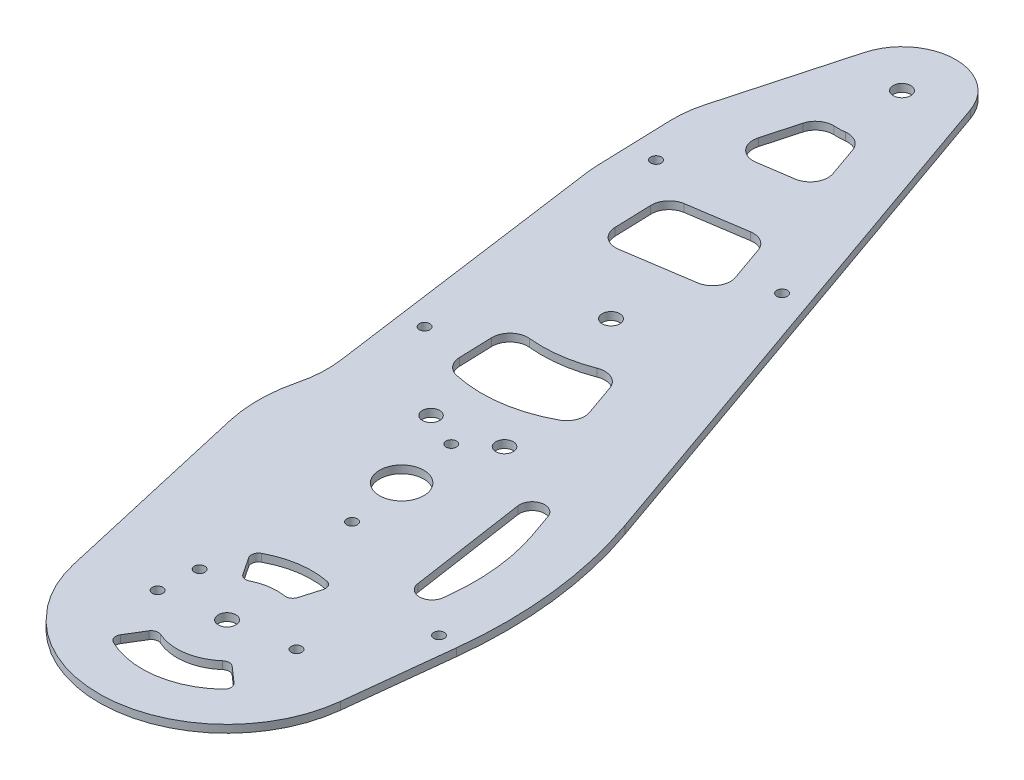
SolidWorks part; units mm, degrees
material "2024-T3"
ref_plane "Front Plane" through (0, 0, 0) normal (0, 0, 1) x (1, 0, 0)
ref_plane "Top Plane" through (0, 0, 0) normal (0, 1, 0) x (1, 0, 0)
ref_plane "Right Plane" through (0, 0, 0) normal (1, 0, 0) x (0, 0, -1)
sketch "Sketch1" plane through (0, 0, 0) normal (0, 1, 0) x (1, 0, 0)
  line L0 (-52.8408, -53.4809) -> (-39.9436, -109.9388)
  line L1 (30.3798, -105.849) -> (33.6155, -76.789)
  line L2 (27.5639, -23.7203) -> (-24.6842, 124.9398)
  line L3 (-53.2991, 123.942) -> (-62.8551, 89.1791)
  line L4 (-63.9122, 80.2517) -> (-63.23, 59.2843)
  line L5 (-62.9652, 56.1657) -> (-52.0063, -23.3829)
  line L6 (-41.9171, 82.2985) -> (-32.3997, 83.6985)
  line L7 (-44.7933, 98.2933) -> (-47.4659, 88.5706)
  line L8 (-28.4102, 90.3032) -> (-31.3828, 98.7609)
  line L9 (-16.9379, 51.6293) -> (-20.3906, 61.4534)
  line L10 (-45.8179, 46.898) -> (-46.153, 57.1955)
  line L11 (-41.9064, 62.3014) -> (-25.8585, 64.7388)
  line L12 (-40.0698, 42.1173) -> (-20.9042, 45.0281)
  line L13 (-4.685, -1.3287) -> (-7.7549, 7.4061)
  line L14 (-36.3858, 3.017) -> (-36.0858, -6.2051)
  line L15 (19.8444, -64.9197) -> (19.6676, -66.5078)
  line L16 (16.8186, -38.3853) -> (14.6523, -32.2214)
  line L17 (12.7267, -66.6322) -> (7.8879, -33.8936)
  line L18 (-0.6531, -86.7536) -> (0.9664, -81.2382)
  line L19 (-13.9187, -88.7684) -> (-17.1027, -83.9826)
  line L20 (6.7887, -112.4755) -> (11.1029, -116.2742)
  line L21 (-13.3878, -115.54) -> (-16.3795, -120.4482)
  arc A0 (-39.9436, -109.9388) -> (-33.4933, -123.6837) centre (-5.1255, -101.985) ccw
  arc A1 (-29.8236, -127.7836) -> (30.3798, -105.849) centre (-5.1255, -101.985) ccw
  arc A2 (33.6155, -76.789) -> (27.5639, -23.7203) centre (-85.6474, -63.5096) ccw
  arc A3 (-24.6842, 124.9398) -> (-53.2991, 123.942) centre (-38.8356, 119.9662) ccw
  arc A4 (-62.8551, 89.1791) -> (-63.9122, 80.2517) centre (-33.9281, 81.2273) ccw
  arc A5 (-63.23, 59.2843) -> (-62.9652, 56.1657) centre (-33.2458, 60.2599) ccw
  arc A6 (-52.6341, -34.8038) -> (-52.0063, -23.3829) centre (-81.7256, -27.4771) ccw
  arc A7 (-52.6341, -34.8038) -> (-52.8408, -53.4809) centre (-13.8453, -44.5729) ccw
  arc A8 (-32.3997, 83.6985) -> (-28.4102, 90.3032) centre (-33.1274, 88.6453) ccw
  arc A9 (-47.4659, 88.5706) -> (-41.9171, 82.2985) centre (-42.6448, 87.2453) ccw
  arc A10 (-31.3828, 98.7609) -> (-36.694, 102.0676) centre (-36.0999, 97.103) ccw
  arc A11 (-39.7253, 101.9619) -> (-44.7933, 98.2933) centre (-39.9721, 96.968) ccw
  arc A12 (-39.7253, 101.9619) -> (-36.694, 102.0676) centre (-38.8356, 119.9662) ccw
  arc A13 (-20.3906, 61.4534) -> (-25.8585, 64.7388) centre (-25.1077, 59.7955) ccw
  arc A14 (-20.9042, 45.0281) -> (-16.9379, 51.6293) centre (-21.655, 49.9715) ccw
  arc A15 (-45.8179, 46.898) -> (-40.0698, 42.1173) centre (-40.8206, 47.0606) ccw
  arc A16 (-41.9064, 62.3014) -> (-46.153, 57.1955) centre (-41.1557, 57.3581) ccw
  arc A17 (-7.7549, 7.4061) -> (-14.2776, 10.4108) centre (-12.4721, 5.7482) ccw
  arc A18 (-7.0048, -7.3744) -> (-4.685, -1.3287) centre (-9.4021, -2.9866) ccw
  arc A19 (-32.1799, -10.922) -> (-7.0048, -7.3744) centre (-24.3039, 24.2874) ccw
  arc A20 (-36.0858, -6.2051) -> (-32.1799, -10.922) centre (-31.0884, -6.0425) ccw
  arc A21 (-30.8916, 8.1548) -> (-36.3858, 3.017) centre (-31.3885, 3.1796) ccw
  arc A22 (-30.8916, 8.1548) -> (-14.2776, 10.4108) centre (-27.3063, 44.0558) ccw
  arc A23 (12.7267, -66.6322) -> (19.6676, -66.5078) centre (16.1891, -66.1205) ccw
  arc A24 (19.8444, -64.9197) -> (16.8186, -38.3853) centre (-39.787, -58.2799) ccw
  arc A25 (14.6523, -32.2214) -> (7.8879, -33.8936) centre (11.3503, -33.3819) ccw
  arc A26 (0.9664, -81.2382) -> (-0.5683, -78.712) centre (-0.9526, -80.6748) ccw
  arc A27 (-2.8913, -88.1645) -> (-0.6531, -86.7536) centre (-2.5721, -86.1901) ccw
  arc A28 (-13.9187, -88.7684) -> (-11.3625, -89.4511) centre (-12.2535, -87.6605) ccw
  arc A29 (-16.3873, -81.1146) -> (-17.1027, -83.9826) centre (-15.4376, -82.8747) ccw
  arc A30 (-0.5683, -78.712) -> (-16.3873, -81.1146) centre (-5.1255, -101.985) ccw
  arc A31 (-2.8913, -88.1645) -> (-11.3625, -89.4511) centre (-5.1255, -101.985) ccw
  arc A32 (11.1542, -119.2295) -> (11.1029, -116.2742) centre (9.7812, -117.7752) ccw
  arc A33 (6.7887, -112.4755) -> (4.143, -112.4776) centre (5.467, -113.9766) ccw
  arc A34 (-10.8607, -114.7564) -> (-13.3878, -115.54) centre (-11.68, -116.5809) ccw
  arc A35 (-16.3795, -120.4482) -> (-15.551, -123.2855) centre (-14.6718, -121.4892) ccw
  arc A36 (-10.8607, -114.7564) -> (4.143, -112.4776) centre (-5.1255, -101.985) ccw
  arc A37 (-15.551, -123.2855) -> (11.1542, -119.2295) centre (-5.1255, -101.985) ccw
  circle A38 centre (-21.1731, -93.5733) radius 1.475
  circle A39 centre (-21.9328, -104.5377) radius 1.475
  circle A40 centre (-5.1255, -101.985) radius 2.455
  circle A41 centre (11.6817, -99.4323) radius 1.475
  circle A42 centre (28.1944, -76.1865) radius 1.475
  circle A43 centre (-11.3677, -60.8858) radius 1.475
  circle A44 centre (-13.8453, -44.5729) radius 6.1681
  circle A45 centre (-8.2509, -21.4709) radius 2.425
  circle A46 centre (-16.3229, -28.2599) radius 1.475
  circle A47 centre (-26.0468, -24.1737) radius 2.425
  circle A48 centre (-56.3662, 68.8988) radius 1.475
  circle A49 centre (-6.6076, 54.2848) radius 1.475
  circle A50 centre (-24.3039, 24.2874) radius 2.455
  circle A51 centre (-48.3826, -3.6449) radius 1.475
  circle A52 centre (-38.8356, 119.9662) radius 2.455
  spline S0 degree 3 poles (-33.4933, -123.6837) (-32.3327, -125.0832) (-31.1307, -126.4498) (-29.8236, -127.7836) knots 0.313139 0.313139 0.313139 0.313139 0.333887 0.333887 0.333887 0.333887
extrude "Boss-Extrude1" add sketch "Sketch1" along normal blind 2.15
